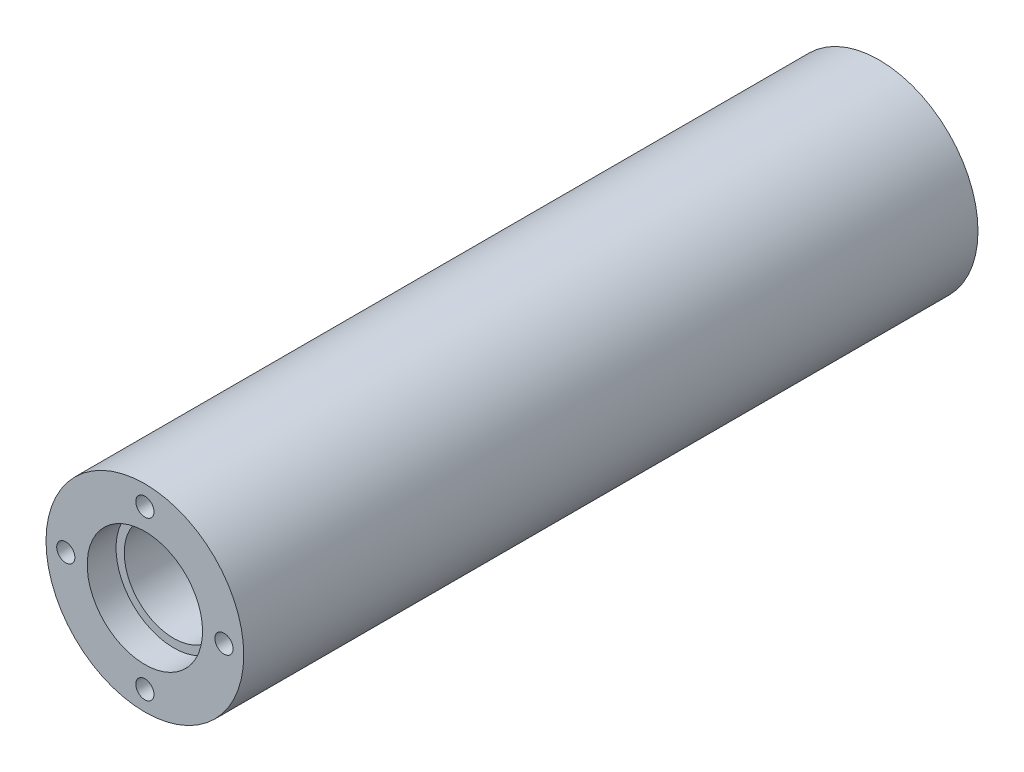
SolidWorks part; units mm, degrees
other "Markup1"
sketch "Sketch4" plane through (19.05, 19.05, 152.4) normal (0.8805, 0.4318, 0.1958) x (0.1841, 0.0692, -0.9805)
ref_plane "Front Plane" through (0, 0, 0) normal (0, 0, 1) x (1, 0, 0)
ref_plane "Top Plane" through (0, 0, 0) normal (0, 1, 0) x (1, 0, 0)
ref_plane "Right Plane" through (0, 0, 0) normal (1, 0, 0) x (0, 0, -1)
sketch "Sketch1" plane through (0, 0, 0) normal (0, 0, 1) x (1, 0, 0)
  circle A0 centre (0, 0) radius 19.05
  circle A1 centre (0, 0) radius 9.525
  dimension "D1" = 38.1
  dimension "D2" = 19.05
extrude "Boss-Extrude1" add sketch "Sketch1" along normal blind 141.4653
sketch "Sketch2" plane through (0, 0, 0) normal (0, 0, -1) x (-1, 0, 0)
  circle A0 centre (0, 15.24) radius 1.7526
  circle A1 centre (15.24, 0) radius 1.7526
  circle A2 centre (0, -15.24) radius 1.7526
  circle A3 centre (-15.24, 0) radius 1.7526
  point P12 (0, 0)
  dimension "D1" = 3.5052
  dimension "D2" = 15.24
  dimension "D3" = 4
extrude "Cut-Extrude1" cut sketch "Sketch2" against normal blind 9.525
sketch "Sketch3" plane through (0, 0, 141.4653) normal (0, 0, 1) x (1, 0, 0)
  circle A0 centre (0, 15.24) radius 1.7526
  circle A1 centre (15.24, 0) radius 1.7526
  circle A2 centre (0, -15.24) radius 1.7526
  circle A3 centre (-15.24, 0) radius 1.7526
  point P2 (0, 0)
  point P9 (0, 0)
  point P12 (0, 0)
  point P15 (0, 0)
  point P16 (0, 0)
  dimension "D2" = 3.5052
  dimension "D1" = 15.24
  dimension "D3" = 4
extrude "Cut-Extrude2" cut sketch "Sketch3" against normal blind 9.525
sketch "Sketch6" plane through (0, 0, 141.4653) normal (0, 0, 1) x (1, 0, 0)
  circle A0 centre (0, 0) radius 11.1125
  dimension "D1" = 22.225
extrude "Cut-Extrude3" cut sketch "Sketch6" against normal blind 5.5562
sketch "Sketch7" plane through (0, 0, 0) normal (0, 0, -1) x (-1, 0, 0)
  circle A0 centre (0, 0) radius 11.1125
  dimension "D1" = 22.225
extrude "Cut-Extrude4" cut sketch "Sketch7" against normal blind 5.5562
